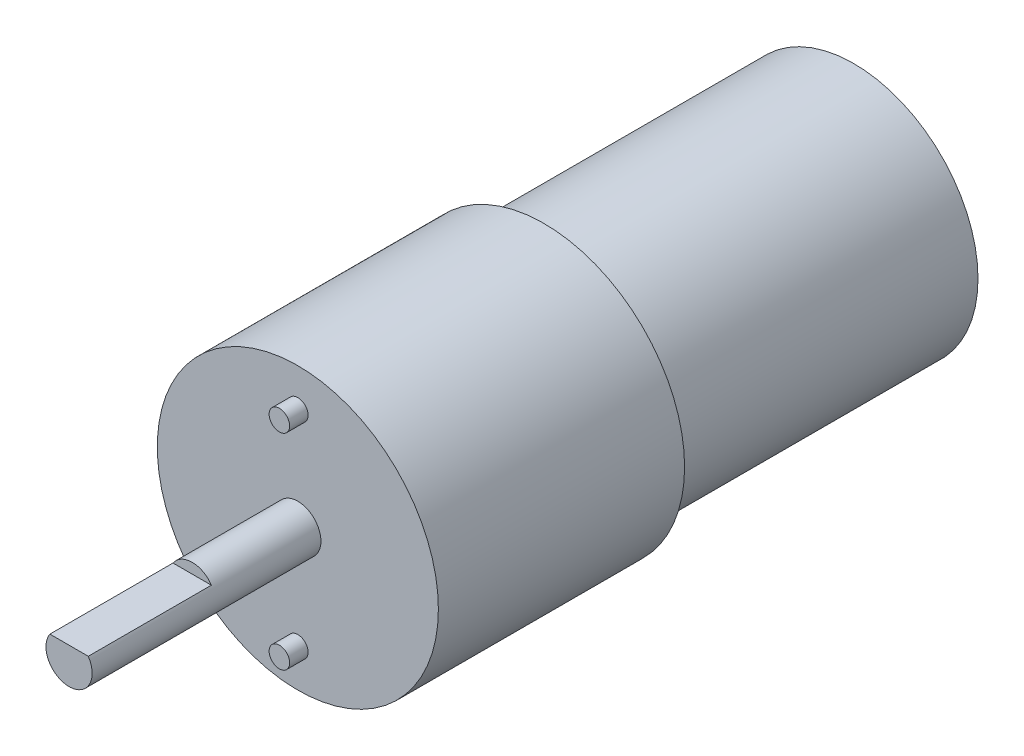
SolidWorks part; units mm, degrees
ref_plane "Front" through (0, 0, 0) normal (0, 0, 1) x (1, 0, 0)
ref_plane "Top" through (0, 0, 0) normal (0, 1, 0) x (1, 0, 0)
ref_plane "Right" through (0, 0, 0) normal (1, 0, 0) x (0, 0, -1)
sketch "Sketch1" plane through (0, 0, 0) normal (0, 0, 1) x (1, 0, 0)
  circle A0 centre (0, 0) radius 12.1
  dimension "D1" = 24.2
extrude "Boss-Extrude1" add sketch "Sketch1" along normal blind 30.2
sketch "Sketch2" plane through (0, 0, 30.2) normal (0, 0, 1) x (1, 0, 0)
  circle A0 centre (0, 0) radius 13.7
  dimension "D1" = 27.4
extrude "Boss-Extrude2" add sketch "Sketch2" along normal blind 24
sketch "Sketch4" plane through (0, 0, 54.2) normal (0, 0, 1) x (1, 0, 0)
  circle A0 centre (0, 0) radius 10
  circle A1 centre (0, 10) radius 1
  circle A2 centre (0, -10) radius 1
  dimension "D1" = 20
  dimension "D2" = 2
  dimension "D3" = 2
extrude "Boss-Extrude3" add sketch "Sketch4" along normal blind 1.8 contours A1 | A2
sketch "Sketch5" plane through (0, 0, 54.2) normal (0, 0, 1) x (1, 0, 0)
  circle A0 centre (0, 0) radius 2.25
  dimension "D1" = 4.5
extrude "Boss-Extrude4" add sketch "Sketch5" along normal blind 22.3
sketch "Sketch6" plane through (0, 0, 76.5) normal (0, 0, 1) x (1, 0, 0)
  line L0 (-1.8708, 1.25) -> (1.8708, 1.25)
  circle A1 centre (0, 0) radius 2.25
  circle A2 centre (0, 0) radius 2.25
  circle M2 centre (0, 0) radius 2.25
  dimension "D2" = 1.25
  dimension "D1" = 0
extrude "Cut-Extrude1" cut sketch "Sketch6" against normal blind 12 contours L0 M2
